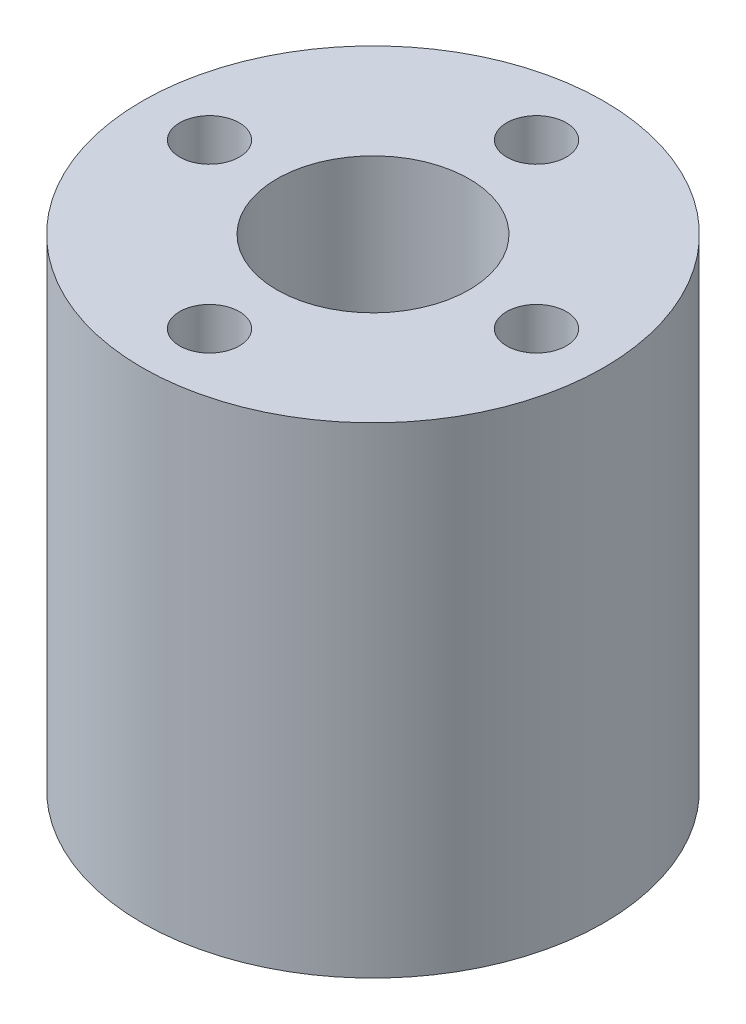
SolidWorks part; units mm, degrees
ref_plane "Front Plane" through (0, 0, 0) normal (0, 0, 1) x (1, 0, 0)
ref_plane "Top Plane" through (0, 0, 0) normal (0, 1, 0) x (1, 0, 0)
ref_plane "Right Plane" through (0, 0, 0) normal (1, 0, 0) x (0, 0, -1)
sketch "Sketch1" plane through (0, 0, 0) normal (0, 1, 0) x (1, 0, 0)
  circle A0 centre (0, 0) radius 8.5 construction
  circle A1 centre (0, 8.5) radius 1.55
  circle A2 centre (8.5, 0) radius 1.55
  circle A3 centre (0, -8.5) radius 1.55
  circle A4 centre (-8.5, 0) radius 1.55
  circle A5 centre (0, 0) radius 5
  circle A6 centre (0, 0) radius 12
  point P14 (0, 0)
  dimension "D1" = 4
extrude "Boss-Extrude1" add sketch "Sketch1" along normal blind 25
